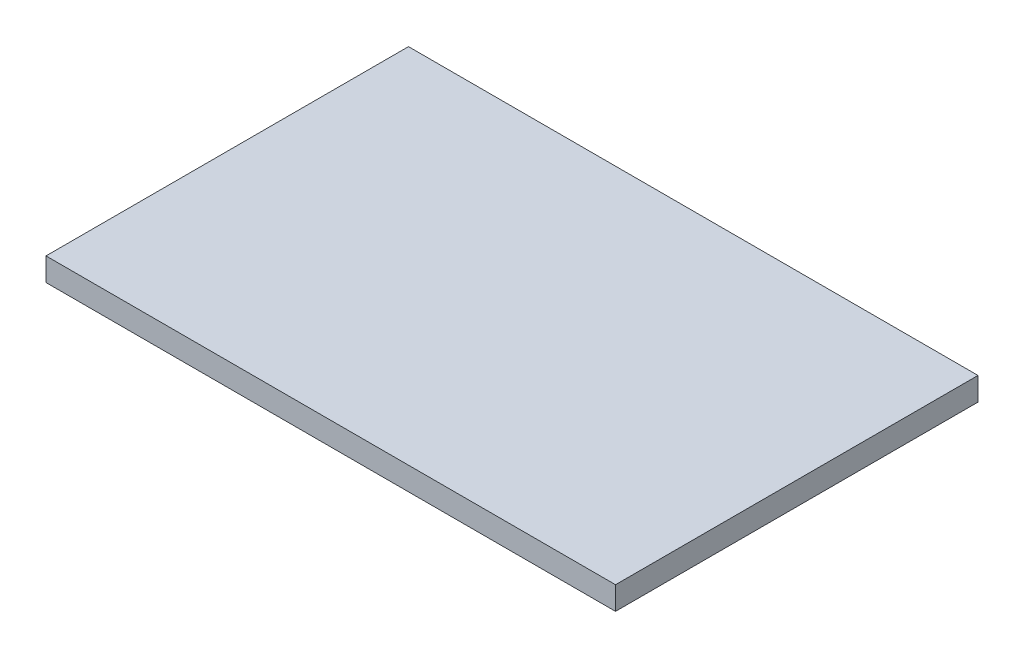
SolidWorks part; units mm, degrees
ref_plane "Alzado" through (0, 0, 0) normal (0, 0, 1) x (1, 0, 0)
ref_plane "Planta" through (0, 0, 0) normal (0, 1, 0) x (1, 0, 0)
ref_plane "Vista lateral" through (0, 0, 0) normal (1, 0, 0) x (0, 0, -1)
sketch "Croquis1" plane through (0, 0, 0) normal (0, 1, 0) x (1, 0, 0)
  line L1 (0, 0) -> (1252.4, 0)
  line L2 (0, 0) -> (0, -797.1)
  line L3 (0, -797.1) -> (1252.4, -797.1)
  line L4 (1252.4, 0) -> (1252.4, -797.1)
  dimension "D1" = 1252.4
  dimension "D2" = 797.1
extrude "Saliente-Extruir1" add sketch "Croquis1" along normal blind 50.8
